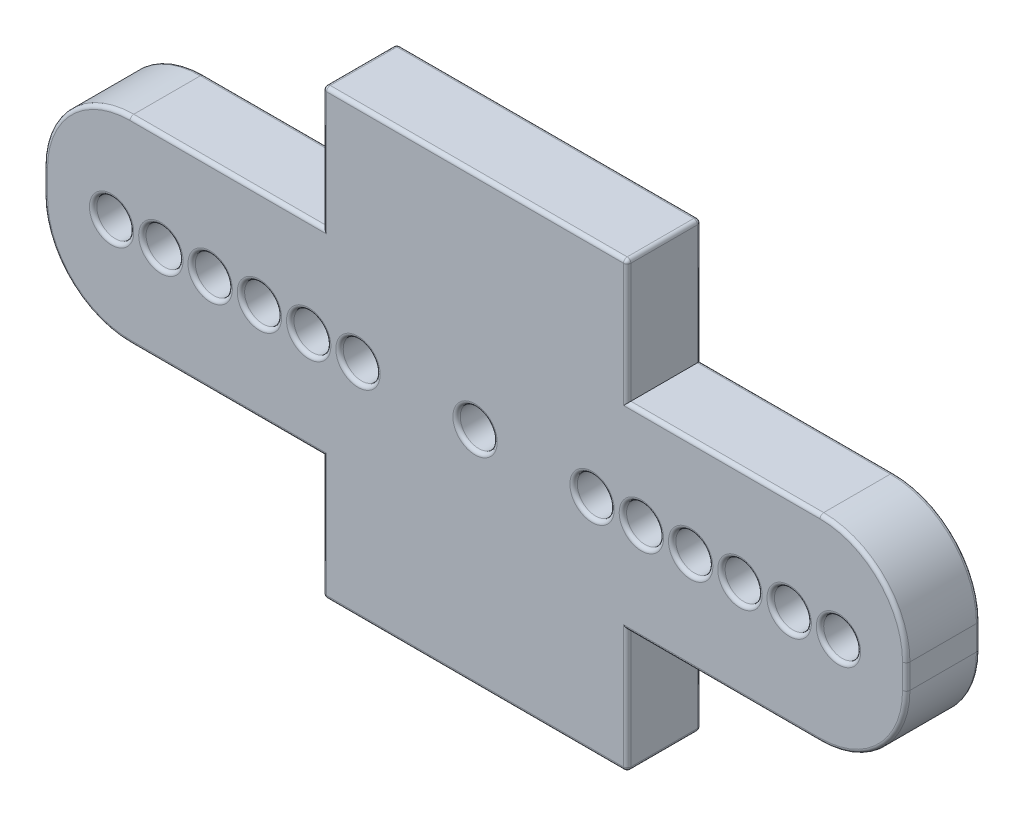
SolidWorks part; units mm, degrees
ref_plane "前视基准面" through (0, 0, 0) normal (0, 0, 1) x (1, 0, 0)
ref_plane "上视基准面" through (0, 0, 0) normal (0, 1, 0) x (1, 0, 0)
ref_plane "右视基准面" through (0, 0, 0) normal (1, 0, 0) x (0, 0, -1)
sketch "草图1" plane through (0, 0, 0) normal (0, 0, 1) x (1, 0, 0)
  line L0 (-17.5, -0.5) -> (-17.5, 0.5)
  line L1 (6.175, -9) -> (-6.175, -9) construction
  line L2 (6.175, -9) -> (6.175, 9) construction
  line L3 (6.175, 9) -> (-6.175, 9) construction
  line L4 (-6.175, -9) -> (-6.175, 9) construction
  line L5 (6.175, -9) -> (-6.175, 9) construction
  line L6 (6.175, 9) -> (-6.175, -9) construction
  line L7 (-17.5, -4) -> (17.5, -4) construction
  line L8 (-17.5, -4) -> (-17.5, 4) construction
  line L9 (-17.5, 4) -> (17.5, 4) construction
  line L10 (17.5, -4) -> (17.5, 4) construction
  line L11 (-17.5, -4) -> (17.5, 4) construction
  line L12 (-17.5, 4) -> (17.5, -4) construction
  line L13 (-14, 4) -> (-6.175, 4)
  line L14 (-6.175, 4) -> (-6.175, 9)
  line L15 (-6.175, 9) -> (6.175, 9)
  line L16 (6.175, 9) -> (6.175, 4)
  line L17 (6.175, 4) -> (14, 4)
  line L18 (17.5, 0.5) -> (17.5, -0.5)
  line L19 (14, -4) -> (6.175, -4)
  line L20 (6.175, -4) -> (6.175, -9)
  line L21 (6.175, -9) -> (-6.175, -9)
  line L22 (-6.175, -9) -> (-6.175, -4)
  line L23 (-6.175, -4) -> (-14, -4)
  circle A0 centre (0, 0) radius 0.75
  arc A1 (14, 4) -> (17.5, 0.5) centre (14, 0.5) cw
  arc A2 (17.5, -0.5) -> (14, -4) centre (14, -0.5) cw
  arc A3 (-17.5, 0.5) -> (-14, 4) centre (-14, 0.5) cw
  arc A4 (-17.5, -0.5) -> (-14, -4) centre (-14, -0.5) ccw
  point P0 (0, 0)
  point P6 (0, 0)
  dimension "D5" = 1.5
  dimension "D6" = 3.5
  dimension "D1" = 8
  dimension "D2" = 35
  dimension "D3" = 12.35
  dimension "D4" = 18
extrude "凸台-拉伸1" add sketch "草图1" along normal mid plane 3
sketch "草图2" plane through (0, 0, -1.5) normal (0, 0, -1) x (-1, 0, 0)
  line L0 (-17.5, -0.5) -> (-17.5, 0.5) construction
  circle A0 centre (-14.75, 0) radius 0.75
  circle A1 centre (-12.75, 0) radius 0.75
  circle A2 centre (-10.75, 0) radius 0.75
  circle A3 centre (-8.75, 0) radius 0.75
  circle A4 centre (-6.75, 0) radius 0.75
  circle A5 centre (-4.75, 0) radius 0.75
  dimension "D1" = 1.5
  dimension "D2" = 2.75
  dimension "D3" = 6
  dimension "D4" = 2
extrude "切除-拉伸1" cut sketch "草图2" against normal through all
mirror "镜向1" about plane through (0, 0, 0) normal (1, 0, 0) of "切除-拉伸1"
fillet "圆角1" radius 0.15 62 edges at (-4, 0, -1.5) (-4, 0, 1.5) (-6, 0, -1.5) (-6, 0, 1.5) (-8, 0, -1.5) (-8, 0, 1.5) (-10, 0, -1.5) (-10, 0, 1.5) (-12, 0, -1.5) (-12, 0, 1.5) (-14, 0, -1.5) (-14, 0, 1.5) (4, 0, -1.5) (4, 0, 1.5) (6, 0, -1.5) (6, 0, 1.5) (8, 0, -1.5) (8, 0, 1.5) (10, 0, -1.5) (10, 0, 1.5) (12, 0, -1.5) (12, 0, 1.5) (14, 0, -1.5) (14, 0, 1.5) (0.75, 0, -1.5) (0.75, 0, 1.5) (0, 9, -1.5) (-6.175, 6.5, -1.5) (-10.0875, 4, -1.5) (-17.5, 0, -1.5) (-10.0875, -4, -1.5) (-6.175, -6.5, -1.5) (0, -9, -1.5) (6.175, -6.5, -1.5) (10.0875, -4, -1.5) (17.5, 0, -1.5) (10.0875, 4, -1.5) (6.175, 6.5, -1.5) (0, 9, 1.5) (-6.175, 6.5, 1.5) (-10.0875, 4, 1.5) (-17.5, 0, 1.5) (-10.0875, -4, 1.5) (-6.175, -6.5, 1.5) (0, -9, 1.5) (6.175, -6.5, 1.5) (10.0875, -4, 1.5) (17.5, 0, 1.5) (10.0875, 4, 1.5) (6.175, 6.5, 1.5) (6.175, 9, 0) (6.175, -9, 0) (-6.175, 9, 0) (-6.175, -9, 0) (-16.4749, 2.9749, -1.5) (-16.4749, -2.9749, -1.5) (16.4749, -2.9749, -1.5) (16.4749, 2.9749, -1.5) (-16.4749, 2.9749, 1.5) (-16.4749, -2.9749, 1.5) (16.4749, -2.9749, 1.5) (16.4749, 2.9749, 1.5)
